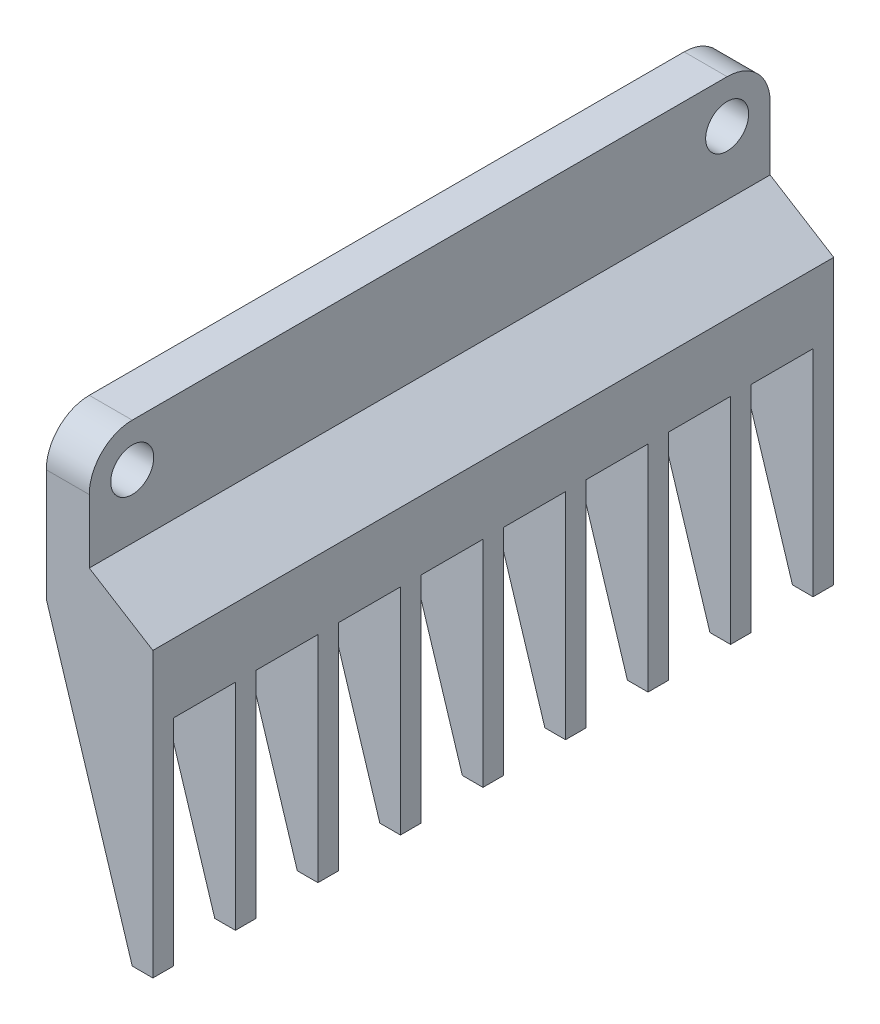
SolidWorks part; units mm, degrees
ref_plane "Front Plane" through (0, 0, 0) normal (0, 0, 1) x (1, 0, 0)
ref_plane "Top Plane" through (0, 0, 0) normal (0, 1, 0) x (1, 0, 0)
ref_plane "Right Plane" through (0, 0, 0) normal (1, 0, 0) x (0, 0, -1)
sketch "Sketch1" plane through (0, 0, 0) normal (0, 0, 1) x (1, 0, 0)
  line L0 (0, 0) -> (3.048, 0)
  line L1 (3.048, 0) -> (3.048, 41.91)
  line L2 (3.048, 41.91) -> (-6.35, 47.752)
  line L3 (-6.35, 47.752) -> (-6.35, 63.5)
  line L4 (-6.35, 63.5) -> (-12.7, 63.5)
  line L5 (-12.7, 63.5) -> (-12.7, 40.64)
  line L6 (-12.7, 40.64) -> (0, 0)
  dimension "D1" = 3.048
  dimension "D2" = 6.35
  dimension "D3" = 40.64
  dimension "D4" = 15.748
  dimension "D5" = 21.59
  dimension "D6" = 15.748
  dimension "D7" = 63.5
extrude "Boss-Extrude1" add sketch "Sketch1" along normal blind 100.584
fillet "Fillet1" radius 6.35 2 edges at (-9.525, 63.5, 0) (-9.525, 63.5, 100.584)
sketch "Sketch6" plane through (-6.35, 0, 0) normal (1, 0, 0) x (0, 0, -1)
  circle A0 centre (-94.234, 57.15) radius 3.175
  circle A1 centre (-6.35, 57.15) radius 3.175
  dimension "D1" = 6.35
  dimension "D2" = 6.35
extrude "Cut-Extrude2" cut sketch "Sketch6" against normal mid plane 125.984
sketch "Sketch7" plane through (3.048, 0, 0) normal (1, 0, 0) x (0, 0, -1)
  line L0 (-100.584, 0) -> (0, 0) construction
  line L1 (-97.536, 0) -> (-88.392, 0)
  line L2 (-97.536, 0) -> (-97.536, 31.75)
  line L3 (-97.536, 31.75) -> (-88.392, 31.75)
  line L4 (-88.392, 0) -> (-88.392, 31.75)
  line L5 (-100.584, 0) -> (-100.584, 41.91) construction
  line L6 (-85.344, 0) -> (-85.344, 31.75)
  line L7 (-85.344, 0) -> (-76.2, 0)
  line L8 (-76.2, 0) -> (-76.2, 31.75)
  line L9 (-85.344, 31.75) -> (-76.2, 31.75)
  line L10 (-73.152, 0) -> (-73.152, 31.75)
  line L11 (-73.152, 0) -> (-64.008, 0)
  line L12 (-64.008, 0) -> (-64.008, 31.75)
  line L13 (-73.152, 31.75) -> (-64.008, 31.75)
  line L14 (-60.96, 0) -> (-60.96, 31.75)
  line L15 (-60.96, 0) -> (-51.816, 0)
  line L16 (-51.816, 0) -> (-51.816, 31.75)
  line L17 (-60.96, 31.75) -> (-51.816, 31.75)
  line L18 (-48.768, 0) -> (-48.768, 31.75)
  line L19 (-48.768, 0) -> (-39.624, 0)
  line L20 (-39.624, 0) -> (-39.624, 31.75)
  line L21 (-48.768, 31.75) -> (-39.624, 31.75)
  line L22 (-36.576, 0) -> (-36.576, 31.75)
  line L23 (-36.576, 0) -> (-27.432, 0)
  line L24 (-27.432, 0) -> (-27.432, 31.75)
  line L25 (-36.576, 31.75) -> (-27.432, 31.75)
  line L26 (-24.384, 0) -> (-24.384, 31.75)
  line L27 (-24.384, 0) -> (-15.24, 0)
  line L28 (-15.24, 0) -> (-15.24, 31.75)
  line L29 (-24.384, 31.75) -> (-15.24, 31.75)
  line L30 (-12.192, 0) -> (-12.192, 31.75)
  line L31 (-12.192, 0) -> (-3.048, 0)
  line L32 (-3.048, 0) -> (-3.048, 31.75)
  line L33 (-12.192, 31.75) -> (-3.048, 31.75)
  line L38 (0, 0) -> (0, 41.91)
  line L39 (0, 41.91) -> (-100.584, 41.91)
  line L40 (-100.584, 41.91) -> (-100.584, 0)
  line L41 (-100.584, 0) -> (0, 0)
  line L42 (0, 0) -> (0, 41.91)
  line L43 (0, 41.91) -> (-100.584, 41.91)
  line L44 (-100.584, 41.91) -> (-100.584, 0)
  line L45 (-100.584, 0) -> (0, 0)
  line M16 (-100.584, 0) -> (0, 0)
  dimension "D1" = 31.75
  dimension "D2" = 3.048
  dimension "D3" = 9.144
  dimension "D5" = 12.192
  dimension "D6" = 0
  dimension "D4" = 8
extrude "Cut-Extrude5" cut sketch "Sketch7" against normal through all contours L4 L3 L2 M16 | L9 L6 L8 M16 | L13 L10 L12 M16 | L17 L14 L16 M16 | L21 L18 L20 M16 | L25 L22 L24 M16 | L29 L26 L28 M16 | L33 L30 L32 M16
